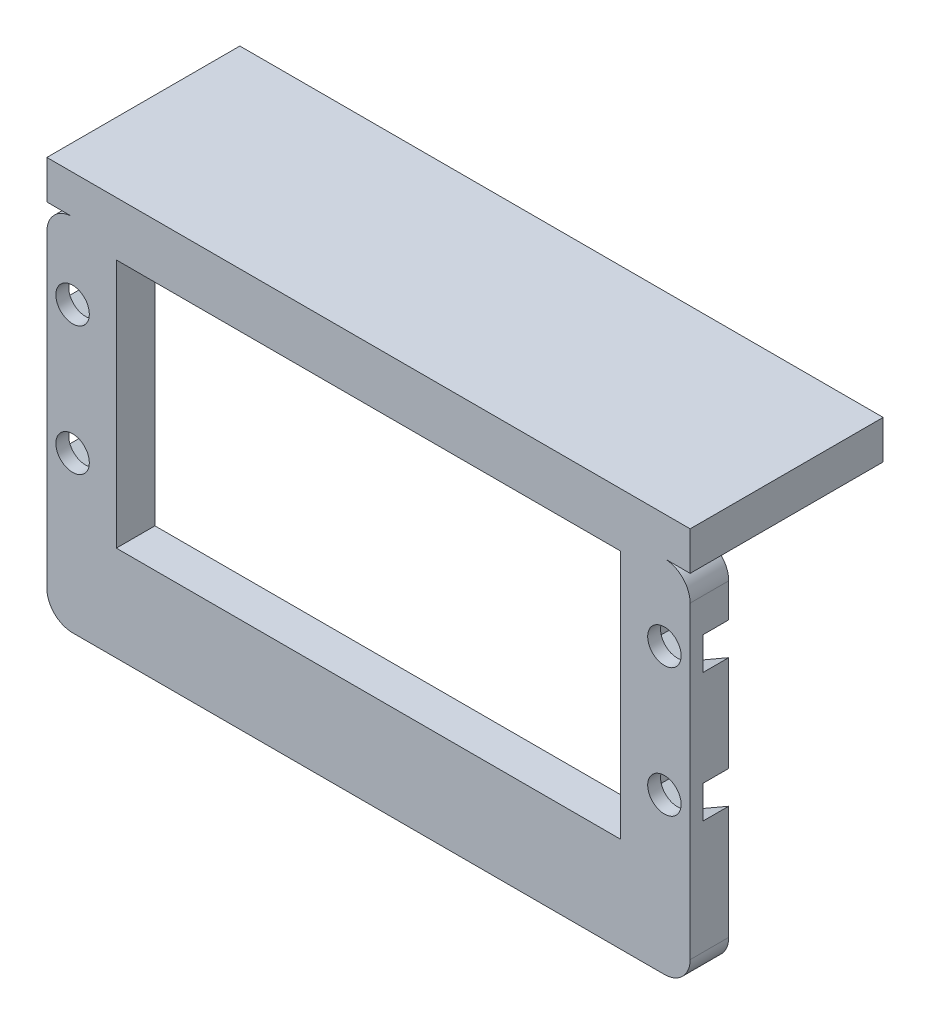
SolidWorks part; units mm, degrees
ref_plane "Front Plane" through (0, 0, 0) normal (0, 0, 1) x (1, 0, 0)
ref_plane "Top Plane" through (0, 0, 0) normal (0, 1, 0) x (1, 0, 0)
ref_plane "Right Plane" through (0, 0, 0) normal (1, 0, 0) x (0, 0, -1)
sketch "Sketch1" plane through (0, 0, 0) normal (0, 0, 1) x (1, 0, 0)
  line L0 (-23, -28) -> (23, -28)
  line L1 (25, -26) -> (25, -2)
  line L2 (23, 0) -> (-23, 0)
  line L3 (-25, -2) -> (-25, -26)
  arc A0 (23, -28) -> (25, -26) centre (23, -26) ccw
  arc A1 (25, -2) -> (23, 0) centre (23, -2) ccw
  arc A2 (-23, 0) -> (-25, -2) centre (-23, -2) ccw
  arc A3 (-25, -26) -> (-23, -28) centre (-23, -26) ccw
extrude "Boss-Extrude1" add sketch "Sketch1" along normal blind 3
sketch "Sketch2" plane through (0, 0, 0) normal (0, 0, 1) x (1, 0, 0)
  line L0 (-19.6, -20.6) -> (19.6, -20.6)
  line L1 (19.6, -20.6) -> (19.6, -1.2)
  line L2 (19.6, -1.2) -> (-19.6, -1.2)
  line L3 (-19.6, -1.2) -> (-19.6, -20.6)
extrude "Cut-Extrude1" cut sketch "Sketch2" against normal through all and the other way through all
sketch "Sketch3" plane through (0, 0, 0) normal (0, 0, 1) x (1, 0, 0)
  circle A0 centre (23, -5.9) radius 1.3
  circle A1 centre (23, -15.9) radius 1.3
  circle A2 centre (-23, -5.9) radius 1.3
  circle A3 centre (-23, -15.9) radius 1.3
extrude "Cut-Extrude2" cut sketch "Sketch3" against normal through all and the other way through all
sketch "Sketch4" plane through (0, 0, 0) normal (0, 0, 1) x (1, 0, 0)
  line L0 (25.1, -4.6876) -> (23, -3.4751)
  line L1 (23, -3.4751) -> (20.9, -4.6876)
  line L2 (20.9, -4.6876) -> (20.9, -7.1124)
  line L3 (20.9, -7.1124) -> (23, -8.3249)
  line L4 (23, -8.3249) -> (25.1, -7.1124)
  line L5 (25.1, -7.1124) -> (25.1, -4.6876)
  line L6 (25.1, -14.6876) -> (23, -13.4751)
  line L7 (23, -13.4751) -> (20.9, -14.6876)
  line L8 (20.9, -14.6876) -> (20.9, -17.1124)
  line L9 (20.9, -17.1124) -> (23, -18.3249)
  line L10 (23, -18.3249) -> (25.1, -17.1124)
  line L11 (25.1, -17.1124) -> (25.1, -14.6876)
  line L12 (-20.9, -4.6876) -> (-23, -3.4751)
  line L13 (-23, -3.4751) -> (-25.1, -4.6876)
  line L14 (-25.1, -4.6876) -> (-25.1, -7.1124)
  line L15 (-25.1, -7.1124) -> (-23, -8.3249)
  line L16 (-23, -8.3249) -> (-20.9, -7.1124)
  line L17 (-20.9, -7.1124) -> (-20.9, -4.6876)
  line L18 (-20.9, -14.6876) -> (-23, -13.4751)
  line L19 (-23, -13.4751) -> (-25.1, -14.6876)
  line L20 (-25.1, -14.6876) -> (-25.1, -17.1124)
  line L21 (-25.1, -17.1124) -> (-23, -18.3249)
  line L22 (-23, -18.3249) -> (-20.9, -17.1124)
  line L23 (-20.9, -17.1124) -> (-20.9, -14.6876)
extrude "Cut-Extrude3" cut sketch "Sketch4" along normal blind 2
sketch "Sketch5" plane through (0, 0, 0) normal (0, 1, 0) x (1, 0, 0)
  line L0 (-25, 12) -> (25, 12)
  line L1 (25, 12) -> (25, -3)
  line L2 (25, -3) -> (-25, -3)
  line L3 (-25, -3) -> (-25, 12)
extrude "Boss-Extrude2" add sketch "Sketch5" along normal blind 3
